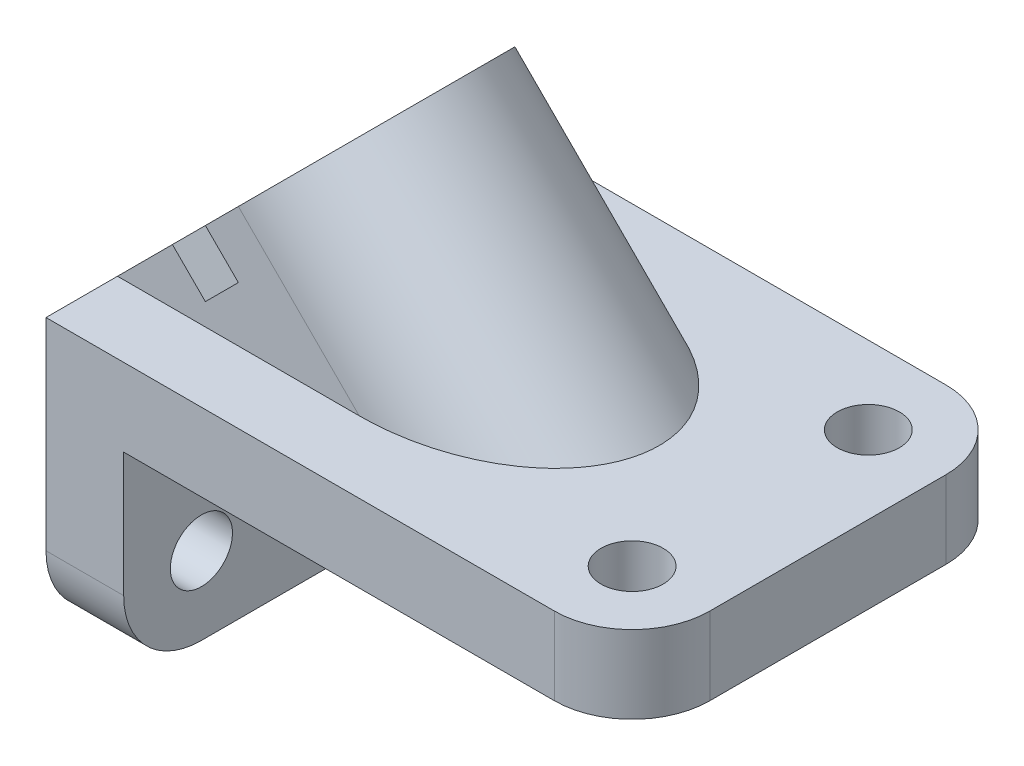
SolidWorks part; units mm, degrees
material "CA"
ref_plane "Front Plane" through (0, 0, 0) normal (0, 0, 1) x (1, 0, 0)
ref_plane "Top Plane" through (0, 0, 0) normal (0, 1, 0) x (1, 0, 0)
ref_plane "Right Plane" through (0, 0, 0) normal (1, 0, 0) x (0, 0, -1)
sketch "Sketch1" plane through (0, 0, 0) normal (0, 0, 1) x (1, 0, 0)
  line L0 (-100.2128, -90) -> (-100.2128, 0)
  line L1 (-100.2128, 0) -> (88.3721, 0)
  line L2 (-100.2128, -90) -> (-75.2128, -90)
  line L3 (-75.2128, -90) -> (-75.2128, -25)
  line L4 (-75.2128, -25) -> (88.3721, -25)
  line L5 (88.3721, -25) -> (88.3721, 0)
  point P6 (86.3556, -25)
  point P8 (53.7592, -25)
  dimension "D1" = 90
  dimension "D2" = 25
  dimension "D3" = 25
extrude "Boss-Extrude1" add sketch "Sketch1" along normal mid plane 126
fillet "Fillet1" radius 25 4 edges at (-87.7128, -90, -63) (-87.7128, -90, 63) (88.3721, -12.5, -63) (88.3721, -12.5, 63)
sketch "Sketch2" plane through (0, -25, 0) normal (0, -1, 0) x (1, 0, 0)
  circle A0 centre (63.3721, -38) radius 10
  circle A1 centre (63.3721, 38) radius 10
  arc A2 (63.3721, -63) -> (88.3721, -38) centre (63.3721, -38) ccw construction
  arc A3 (88.3721, 38) -> (63.3721, 63) centre (63.3721, 38) ccw construction
  dimension "D1" = 20
extrude "Cut-Extrude1" cut sketch "Sketch2" against normal blind 126
sketch "Sketch3" plane through (-100.2128, 0, 0) normal (-1, 0, 0) x (0, 0, 1)
  circle A0 centre (-38, -65) radius 10
  circle A1 centre (38, -65) radius 10
  arc A2 (-63, -65) -> (-38, -90) centre (-38, -65) ccw construction
  arc A3 (38, -90) -> (63, -65) centre (38, -65) ccw construction
  dimension "D1" = 20
extrude "Cut-Extrude2" cut sketch "Sketch3" against normal blind 126
sketch "Sketch4" plane through (0, 0, 0) normal (0, 0, 1) x (1, 0, 0)
  line L0 (-100.2128, 0) -> (-61.3219, 38.8909)
  line L1 (63.3721, 0) -> (-100.2128, 0) construction
  line L2 (-61.3219, 38.8909) -> (-22.431, 0)
  line L3 (-22.431, 0) -> (-100.2128, 0)
  dimension "D1" = 55
  dimension "D2" = 45
  dimension "D3" = 45
extrude "Boss-Extrude2" add sketch "Sketch4" along normal mid plane 80
sketch "Sketch10" plane through (-50.1064, 50.1064, 0) normal (-0.7071, 0.7071, 0) x (0, 0, 1)
  line L0 (40, -15.8611) -> (-40, -15.8611) construction
  circle A0 centre (0, -15.8611) radius 40
extrude "Boss-Extrude6" add sketch "Sketch10" against normal up to next
sketch "Sketch11" plane through (-50.1064, 50.1064, 0) normal (-0.7071, 0.7071, 0) x (0, 0, 1)
  line L0 (0, -70.8611) -> (0, 24.1389) construction
  line L1 (40, -70.8611) -> (-40, -70.8611) construction
  circle A0 centre (0, 4.1389) radius 15
  arc A2 (40, -15.8611) -> (-40, -15.8611) centre (0, -15.8611) ccw construction
  point P4 (0, 0)
  dimension "D1" = 30
  dimension "D2" = 75
extrude "Cut-Extrude11" cut sketch "Sketch11" against normal through all
sketch "Sketch12" plane through (0, 0, 40) normal (0, 0, 1) x (1, 0, 0)
  line L0 (-82.5351, 17.6777) -> (-71.9285, 7.0711)
  line L1 (-71.9285, 7.0711) -> (-61.3219, 17.6777)
  line L2 (-61.3219, 17.6777) -> (-71.9285, 28.2843)
  line L3 (-100.2128, 0) -> (-22.431, 0)
  line L4 (-22.431, 0) -> (-61.3219, 38.8909)
  line L5 (-61.3219, 38.8909) -> (-100.2128, 0)
  line L8 (-71.9285, 28.2843) -> (-82.5351, 17.6777)
  point P5 (-66.6252, 12.3744)
  point P8 (-77.2318, 12.3744)
  dimension "D2" = 15
  dimension "D3" = 15
  dimension "D4" = 25
  dimension "D1" = 0
extrude "Cut-Extrude12" cut sketch "Sketch12" against normal blind 90
